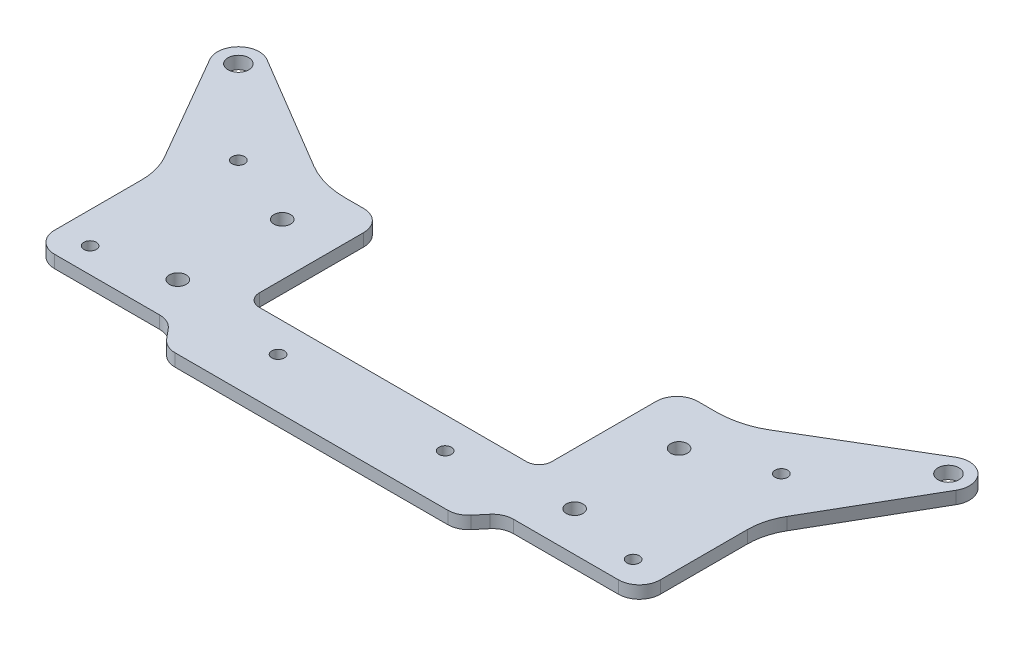
SolidWorks part; units mm, degrees
material "Thornel Mat VMA"
ref_plane "前视基准面" through (0, 0, 0) normal (0, 0, 1) x (1, 0, 0)
ref_plane "上视基准面" through (0, 0, 0) normal (0, 1, 0) x (1, 0, 0)
ref_plane "右视基准面" through (0, 0, 0) normal (1, 0, 0) x (0, 0, -1)
sketch "草图1" plane through (0, 0, 0) normal (0, 1, 0) x (1, 0, 0)
  line L0 (-85, 0) -> (85, 0) construction
  line L1 (0, 0) -> (0, -39.5) construction
  line L2 (-65, -55.5) -> (65, -55.5) construction
  line L3 (-47.5, -52) -> (47.5, -52) construction
  line L4 (-47.5, -52) -> (-47.5, -27) construction
  line L5 (-47.5, -27) -> (47.5, -27) construction
  line L6 (47.5, -52) -> (47.5, -27) construction
  line L7 (-47.5, -52) -> (47.5, -27) construction
  line L8 (-47.5, -27) -> (47.5, -52) construction
  line L9 (-72.5, -61.5) -> (-40, -61.5)
  line L10 (35, -15) -> (50, -15)
  line L11 (-72.5, -35.6699) -> (-72.5, -61.5)
  line L12 (-40, -61.5) -> (-34.9654, -67.5)
  line L13 (-34.9654, -67.5) -> (34.9654, -67.5)
  line L14 (34.9654, -67.5) -> (40, -61.5)
  line L15 (40, -61.5) -> (72.5, -61.5)
  line L16 (-74.5096, -28.1699) -> (-89.3301, -2.5)
  line L22 (72.5, -35.6699) -> (72.5, -61.5)
  line L23 (-35, -15) -> (-35, -45)
  line L24 (74.5096, -28.1699) -> (89.3301, -2.5)
  line L25 (-82.444, 4.2973) -> (-50, -15)
  line L26 (-50, -15) -> (-35, -15)
  line L27 (82.444, 4.2973) -> (50, -15)
  line L28 (-32, -48) -> (32, -48)
  line L29 (35, -45) -> (35, -15)
  circle A0 centre (85, 0) radius 2.5
  circle A1 centre (-85, 0) radius 2.5
  circle A2 centre (47.5, -27) radius 2
  circle A3 centre (47.5, -52) radius 2
  circle A4 centre (-47.5, -52) radius 2
  circle A5 centre (-47.5, -27) radius 2
  arc A6 (89.3301, -2.5) -> (82.444, 4.2973) centre (85, 0) ccw
  arc A7 (-82.444, 4.2973) -> (-89.3301, -2.5) centre (-85, 0) ccw
  circle A8 centre (-20, -55.5) radius 1.5
  circle A9 centre (20, -55.5) radius 1.5
  circle A10 centre (65, -55.5) radius 1.5
  circle A11 centre (-65, -55.5) radius 1.5
  arc A12 (-35, -45) -> (-32, -48) centre (-32, -45) ccw
  arc A13 (32, -48) -> (35, -45) centre (32, -45) ccw
  arc A14 (-72.5, -35.6699) -> (-74.5096, -28.1699) centre (-87.5, -35.6699) ccw
  arc A16 (72.5, -35.6699) -> (74.5096, -28.1699) centre (87.5, -35.6699) cw
  circle A26 centre (65, -20) radius 1.5
  circle A27 centre (-65, -20) radius 1.5
  point P34 (-35, -48)
  point P38 (35, -48)
  dimension "D2" = 5
  dimension "D5" = 4
  dimension "D6" = 10
  dimension "D8" = 40
  dimension "D9" = 45
  dimension "D10" = 3
  dimension "D13" = 7.5
  dimension "D18" = 20
  dimension "D19" = 130
  dimension "D20" = 15
  dimension "D22" = 4
  dimension "D25" = 70
  dimension "D38" = 3
  dimension "D16" = 3
  dimension "D1" = 170
  dimension "D3" = 25
  dimension "D4" = 95
  dimension "D7" = 55.5
  dimension "D14" = 80
  dimension "D15" = 6
  dimension "D17" = 20
  dimension "D21" = 60
  dimension "D23" = 15
  dimension "D24" = 100
  dimension "D12" = 145
  dimension "D11" = 6
extrude "凸台-拉伸1" add sketch "草图1" along normal blind 3
fillet "圆角1" radius 20 2 edges at (50, 1.5, 15) (-50, 1.5, 15)
fillet "圆角2" radius 5 8 edges at (72.5, 1.5, 61.5) (-72.5, 1.5, 61.5) (40, 1.5, 61.5) (34.9654, 1.5, 67.5) (-34.9654, 1.5, 67.5) (-40, 1.5, 61.5) (35, 1.5, 15) (-35, 1.5, 15)
